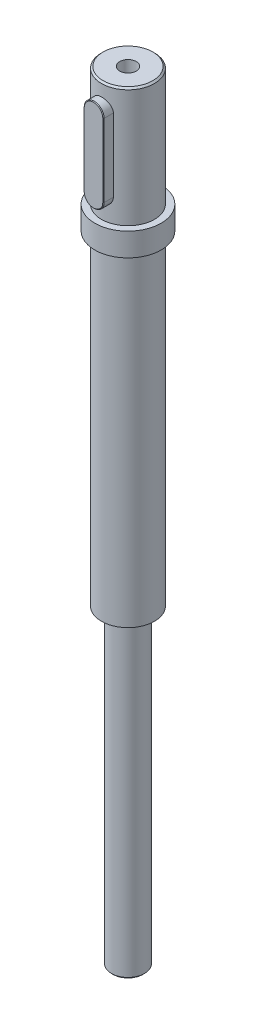
SolidWorks part; units mm, degrees
ref_plane "前视基准面" through (0, 0, 0) normal (0, 0, 1) x (1, 0, 0)
ref_plane "上视基准面" through (0, 0, 0) normal (0, 1, 0) x (1, 0, 0)
ref_plane "右视基准面" through (0, 0, 0) normal (1, 0, 0) x (0, 0, -1)
other "Configuration Table"
sketch "草图1" plane through (0, 0, 0) normal (0, 1, 0) x (1, 0, 0)
  circle A0 centre (0, 0) radius 2.5
  dimension "D1" = 5
extrude "凸台-拉伸1" add sketch "草图1" along normal blind 47
sketch "草图2" plane through (0, 0, 0) normal (0, 1, 0) x (1, 0, 0)
  circle A0 centre (0, 0) radius 4
  dimension "D1" = 8
extrude "凸台-拉伸2" add sketch "草图2" along normal blind 49 from surface at 47 starting at face at (0, 47, 2.5)
sketch "草图3" plane through (0, 0, 0) normal (0, 1, 0) x (1, 0, 0)
  circle A0 centre (0, 0) radius 5
  dimension "D1" = 10
extrude "凸台-拉伸3" add sketch "草图3" along normal blind 3.5 from surface at 96 starting at face at (0, 96, 4)
sketch "草图4" plane through (0, 0, 0) normal (0, 1, 0) x (1, 0, 0)
  circle A0 centre (0, 0) radius 4
  dimension "D1" = 8
extrude "凸台-拉伸4" add sketch "草图4" along normal blind 18 from surface at 99.5 starting at face at (0, 99.5, 5)
sketch "草图6" plane through (0, 0, 0) normal (0, 1, 0) x (1, 0, 0)
  point P0 (0, 0)
hole_wizard "M3 螺纹孔1" positions "3D草图3" profile "草图9" tap size "M3" standard "ISO"
sketch3d "3D草图3"
  point P0 (0, 0, 0)
  point P3 (0, 0, 0)
  point P5 (0, 117.5, 0)
sketch "草图9" plane through (0, 117.5, 0) normal (1, 0, 0) x (0, 0, 1)
  line L0 (0, 0) -> (0, 10.7511)
  line L1 (0, 10.7511) -> (1.25, 10)
  line L2 (1.25, 10) -> (1.25, 0)
  line L5 (1.25, 0) -> (0, 0)
  line L10 (0, 10.7511) -> (-1.25, 10) construction
  line L11 (0, -6.35) -> (0, 107.95) construction
  dimension "螺纹孔钻头直径" = 2.5
  dimension "螺纹孔钻头深度" = 10
  dimension "导头角度" = 118
cosmetic thread "孔螺蚊线3" parameters "D1"=6, "D2"=3
sketch "草图11" plane through (0, 0, 0) normal (0, 0, 1) x (1, 0, 0)
  line L0 (-4, 117.5) -> (4, 99.5) construction
  line L1 (-4, 117.5) -> (4, 117.5) construction
  line L2 (-4, 117.5) -> (-4, 99.5) construction
  line L3 (-4, 99.5) -> (4, 99.5) construction
  line L4 (4, 117.5) -> (4, 99.5) construction
  line L5 (4, 117.5) -> (-4, 99.5) construction
  line L6 (0, 103) -> (0, 114) construction
  line L7 (-1.5, 103) -> (-1.5, 114)
  line L8 (1.5, 103) -> (1.5, 114)
  arc A0 (-1.5, 103) -> (1.5, 103) centre (0, 103) ccw
  arc A1 (1.5, 114) -> (-1.5, 114) centre (0, 114) ccw
  point P8 (0, 108.5)
  dimension "D1" = 1.5
  dimension "D2" = 11
extrude "凸台-拉伸5" add sketch "草图11" along normal blind 3 from offset 2.2
chamfer "倒角1" distance 0.25 angle 45 2 edges at (0, 117.5, 4) (0, 0, 2.5)
chamfer "倒角2" distance 0.1 angle 45 4 edges at (0, 115.5, 5.2) (-1.5, 108.5, 5.2) (0, 101.5, 5.2) (1.5, 108.5, 5.2)
